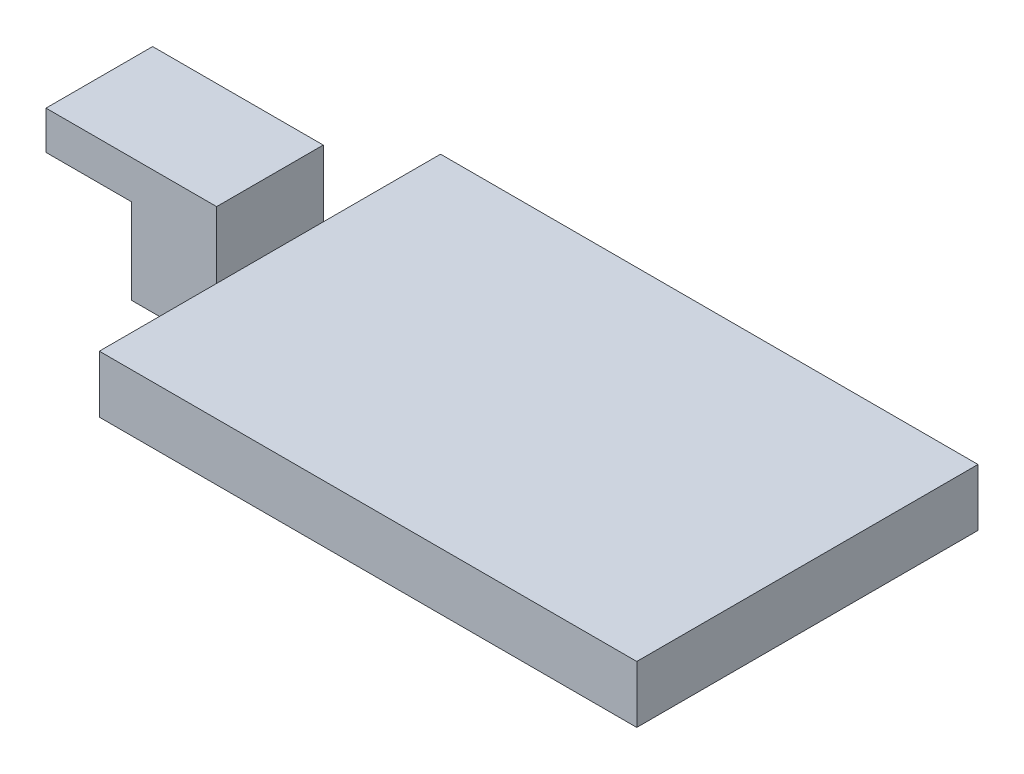
SolidWorks part; units mm, degrees
ref_plane "Front Plane" through (0, 0, 0) normal (0, 0, 1) x (1, 0, 0)
ref_plane "Top Plane" through (0, 0, 0) normal (0, 1, 0) x (1, 0, 0)
ref_plane "Right Plane" through (0, 0, 0) normal (1, 0, 0) x (0, 0, -1)
sketch "Sketch1" plane through (0, 0, 0) normal (0, 1, 0) x (1, 0, 0)
  line L1 (0, 0) -> (10.16, 0)
  line L2 (0, 0) -> (0, 6.35)
  line L3 (0, 6.35) -> (10.16, 6.35)
  line L4 (10.16, 0) -> (10.16, 6.35)
  dimension "D1" = 6.35
  dimension "D2" = 10.16
extrude "Boss-Extrude1" add sketch "Sketch1" along normal blind 2.286
sketch "Sketch2" plane through (0, 0, 0) normal (-1, 0, 0) x (0, 0, 1)
  line L0 (-6.35, 2.286) -> (0, 2.286) construction
  line L1 (-6.0452, 1.9812) -> (-0.2032, 1.9812)
  line L2 (-6.0452, 1.9812) -> (-6.0452, 0.2032)
  line L3 (-6.0452, 0.2032) -> (-0.2032, 0.2032)
  line L4 (-0.2032, 1.9812) -> (-0.2032, 0.2032)
  line L5 (-6.35, 2.286) -> (-6.35, 0) construction
  dimension "D1" = 5.842
  dimension "D2" = 1.778
  dimension "D3" = 0.3048
  dimension "D4" = 0.3048
extrude "Cut-Extrude1" cut sketch "Sketch2" against normal blind 8.89
sketch "Sketch3" plane through (0, 0, 0) normal (0, -1, 0) x (1, 0, 0)
  line L0 (0, 0) -> (10.16, 0) construction
  line L1 (10.16, -6.35) -> (5.08, -6.35)
  line L2 (10.16, -6.35) -> (10.16, 0)
  line L3 (10.16, 0) -> (5.08, 0)
  line L4 (5.08, -6.35) -> (5.08, 0)
  dimension "D1" = 5.08
extrude "Boss-Extrude2" add sketch "Sketch3" along normal blind 5.08
sketch "Sketch4" plane through (10.16, 0, 0) normal (1, 0, 0) x (0, 0, -1)
  line L1 (13.335, -5.08) -> (-6.985, -5.08)
  line L2 (13.335, -5.08) -> (13.335, -1.6764)
  line L3 (13.335, -1.6764) -> (-6.985, -1.6764)
  line L4 (-6.985, -5.08) -> (-6.985, -1.6764)
  line L6 (6.35, -5.08) -> (0, -5.08) construction
  line L7 (0, 2.286) -> (0, -5.08) construction
  dimension "D1" = 20.32
  dimension "D2" = 0
  dimension "D3" = 3.4036
  dimension "D4" = 6.985
  dimension "D5" = 90
extrude "Boss-Extrude3" add sketch "Sketch4" along normal blind 32.004
